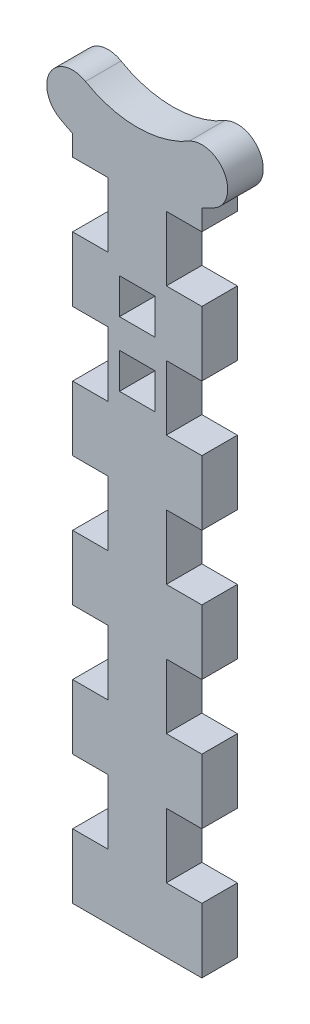
SolidWorks part; units mm, degrees
material "ﾁｰｸ材"
ref_plane "正面" through (0, 0, 0) normal (0, 0, 1) x (1, 0, 0)
ref_plane "平面" through (0, 0, 0) normal (0, 1, 0) x (1, 0, 0)
ref_plane "右側面" through (0, 0, 0) normal (1, 0, 0) x (0, 0, -1)
sketch "ｽｹｯﾁ1" plane through (0, 0, 0) normal (0, 0, 1) x (1, 0, 0)
  line L0 (-10, -21.8174) -> (-10, -125)
  line L1 (-10, -125) -> (10, -125)
  line L2 (10, -125) -> (10, -21.8174)
  arc A0 (-8, -13.8564) -> (8, -13.8564) centre (0, 0) ccw
  arc A1 (8, -13.8564) -> (12, -20.7846) centre (10, -17.3205) cw
  arc A2 (12, -20.7846) -> (10, -21.8174) centre (0, 0) cw
  arc A3 (-12, -20.7846) -> (-8, -13.8564) centre (-10, -17.3205) cw
  arc A4 (-10, -21.8174) -> (-12, -20.7846) centre (0, 0) cw
  point P9 (0, -125)
  dimension "D1" = 16
  dimension "D2" = 24
  dimension "D3" = 60
  dimension "D5" = 20
  dimension "D4" = 125
extrude "ﾎﾞｽ - 押し出し1" add sketch "ｽｹｯﾁ1" along normal blind 5.5
sketch "ｽｹｯﾁ2" plane through (0, 0, 5.5) normal (0, 0, 1) x (1, 0, 0)
  line L0 (-10, -95) -> (-10, -85)
  line L5 (-10, -95) -> (-4.5, -95)
  line L18 (-10, -21.8174) -> (-10, -125) construction
  line L59 (-10, -115) -> (-4.5, -115)
  line L60 (-10, -115) -> (-10, -105)
  line L61 (-10, -105) -> (-4.5, -105)
  line L62 (-4.5, -115) -> (-4.5, -105)
  line L63 (-10, -125) -> (10, -125) construction
  line L64 (-4.5, -95) -> (-4.5, -85)
  line L65 (-10, -85) -> (-4.5, -85)
  line L66 (-10, -75) -> (-10, -65)
  line L67 (-10, -75) -> (-4.5, -75)
  line L68 (-4.5, -75) -> (-4.5, -65)
  line L69 (-10, -65) -> (-4.5, -65)
  line L70 (-10, -55) -> (-10, -45)
  line L71 (-10, -55) -> (-4.5, -55)
  line L72 (-4.5, -55) -> (-4.5, -45)
  line L73 (-10, -45) -> (-4.5, -45)
  line L74 (-10, -35) -> (-10, -25)
  line L75 (-10, -35) -> (-4.5, -35)
  line L76 (-4.5, -35) -> (-4.5, -25)
  line L77 (-10, -25) -> (-4.5, -25)
  line L78 (0, 0) -> (0, -11.9682) construction
  line L79 (10, -105) -> (4.5, -105)
  line L80 (4.5, -115) -> (4.5, -105)
  line L81 (10, -115) -> (4.5, -115)
  line L82 (10, -115) -> (10, -105)
  line L83 (10, -95) -> (4.5, -95)
  line L84 (4.5, -95) -> (4.5, -85)
  line L85 (10, -85) -> (4.5, -85)
  line L86 (10, -95) -> (10, -85)
  line L87 (10, -75) -> (4.5, -75)
  line L88 (4.5, -75) -> (4.5, -65)
  line L89 (10, -65) -> (4.5, -65)
  line L90 (10, -75) -> (10, -65)
  line L91 (10, -55) -> (4.5, -55)
  line L92 (4.5, -55) -> (4.5, -45)
  line L93 (10, -45) -> (4.5, -45)
  line L94 (10, -55) -> (10, -45)
  line L95 (10, -35) -> (4.5, -35)
  line L96 (4.5, -35) -> (4.5, -25)
  line L97 (10, -25) -> (4.5, -25)
  line L98 (10, -35) -> (10, -25)
  dimension "D1" = 5.5
  dimension "D2" = 10
  dimension "D3" = 10
  dimension "D4" = 5
extrude "ｶｯﾄ - 押し出し1" cut sketch "ｽｹｯﾁ2" against normal through all
sketch "ｽｹｯﾁ4" plane through (0, 0, 0) normal (0, 0, -1) x (-1, 0, 0)
  line L0 (0, 0) -> (0, -33.3742) construction
sketch "ｽｹｯﾁ5" plane through (0, 0, 5.5) normal (0, 0, 1) x (1, 0, 0)
  line L1 (-2.75, -37.25) -> (2.75, -37.25)
  line L2 (-2.75, -37.25) -> (-2.75, -42.75)
  line L3 (-2.75, -42.75) -> (2.75, -42.75)
  line L4 (2.75, -37.25) -> (2.75, -42.75)
  line L5 (-2.75, -37.25) -> (2.75, -42.75) construction
  line L6 (-2.75, -42.75) -> (2.75, -37.25) construction
  line L7 (-2.75, -47.25) -> (2.75, -47.25)
  line L8 (-2.75, -47.25) -> (-2.75, -52.75)
  line L9 (-2.75, -52.75) -> (2.75, -52.75)
  line L10 (2.75, -47.25) -> (2.75, -52.75)
  line L11 (-2.75, -47.25) -> (2.75, -52.75) construction
  line L12 (-2.75, -52.75) -> (2.75, -47.25) construction
  point P0 (0, -40)
  point P5 (0, -50)
  dimension "D1" = 5.5
  dimension "D2" = 5.5
  dimension "D3" = 40
  dimension "D4" = 5.5
  dimension "D5" = 5.5
  dimension "D6" = 50
extrude "ｶｯﾄ - 押し出し2" cut sketch "ｽｹｯﾁ5" against normal through all
